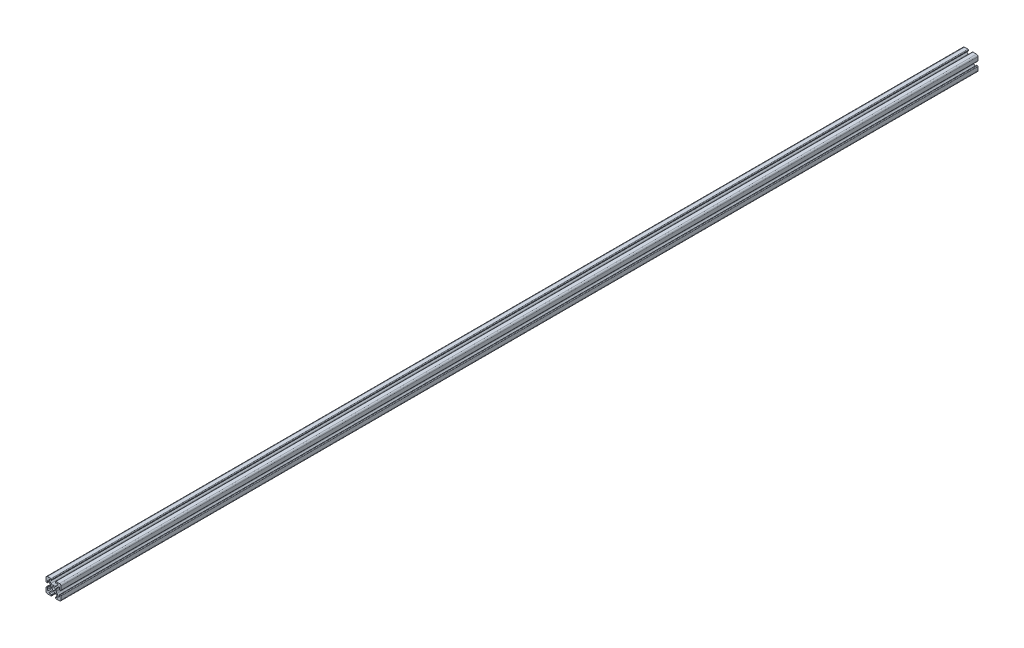
SolidWorks part; units mm, degrees
ref_plane "Front Plane" through (0, 0, 0) normal (0, 0, 1) x (1, 0, 0)
ref_plane "Top Plane" through (0, 0, 0) normal (0, 1, 0) x (1, 0, 0)
ref_plane "Right Plane" through (0, 0, 0) normal (1, 0, 0) x (0, 0, -1)
sketch "Sketch1" plane through (0, 0, 0) normal (0, 0, 1) x (1, 0, 0)
  line L2 (-9.9949, 7.9883) -> (-9.9949, 3.2893)
  line L3 (-7.9883, 9.9949) -> (-3.2893, 9.9949)
  line L4 (-2.5019, 9.2075) -> (-2.5019, 8.4963)
  line L5 (-2.8067, 8.1915) -> (-4.9149, 8.1915)
  line L6 (-5.5076, 6.7606) -> (-3.2528, 4.5058)
  line L7 (-6.7606, 5.5076) -> (-4.5058, 3.2528)
  line L8 (-8.1915, 4.9149) -> (-8.1915, 2.8067)
  line L9 (-8.4963, 2.5019) -> (-9.2075, 2.5019)
  line L11 (-1.1334, 3.6279) -> (1.1334, 3.6279)
  line L12 (-3.6279, 1.1334) -> (-3.6279, -1.1334)
  line L13 (8.4963, 2.5019) -> (9.2075, 2.5019)
  line L14 (8.1915, 4.9149) -> (8.1915, 2.8067)
  line L15 (9.9949, 7.9883) -> (9.9949, 3.2893)
  line L16 (7.9883, 9.9949) -> (3.2893, 9.9949)
  line L17 (2.5019, 9.2075) -> (2.5019, 8.4963)
  line L18 (2.8067, 8.1915) -> (4.9149, 8.1915)
  line L19 (3.6279, 1.1334) -> (3.6279, -1.1334)
  line L20 (5.5076, 6.7606) -> (3.2528, 4.5058)
  line L21 (6.7606, 5.5076) -> (4.5058, 3.2528)
  line L22 (-8.4963, -2.5019) -> (-9.2075, -2.5019)
  line L23 (-8.1915, -4.9149) -> (-8.1915, -2.8067)
  line L24 (-6.7606, -5.5076) -> (-4.5058, -3.2528)
  line L25 (-5.5076, -6.7606) -> (-3.2528, -4.5058)
  line L26 (-2.8067, -8.1915) -> (-4.9149, -8.1915)
  line L27 (-2.5019, -9.2075) -> (-2.5019, -8.4963)
  line L28 (-7.9883, -9.9949) -> (-3.2893, -9.9949)
  line L29 (-9.9949, -7.9883) -> (-9.9949, -3.2893)
  line L30 (9.9949, -7.9883) -> (9.9949, -3.2893)
  line L31 (7.9883, -9.9949) -> (3.2893, -9.9949)
  line L32 (2.5019, -9.2075) -> (2.5019, -8.4963)
  line L33 (2.8067, -8.1915) -> (4.9149, -8.1915)
  line L34 (5.5076, -6.7606) -> (3.2528, -4.5058)
  line L35 (6.7606, -5.5076) -> (4.5058, -3.2528)
  line L36 (8.1915, -4.9149) -> (8.1915, -2.8067)
  line L37 (8.4963, -2.5019) -> (9.2075, -2.5019)
  line L38 (-1.1334, -3.6279) -> (1.1334, -3.6279)
  circle A0 centre (0, 0) radius 2.1463
  arc A1 (-9.9949, 7.9883) -> (-7.9883, 9.9949) centre (-7.9883, 7.9883) cw
  arc A2 (-6.7606, 5.5076) -> (-8.1915, 4.9149) centre (-7.3533, 4.9149) ccw
  arc A3 (-4.9149, 8.1915) -> (-5.5076, 6.7606) centre (-4.9149, 7.3533) ccw
  arc A4 (-3.2893, 9.9949) -> (-2.5019, 9.2075) centre (-3.2893, 9.2075) cw
  arc A5 (-9.9949, 3.2893) -> (-9.2075, 2.5019) centre (-9.2075, 3.2893) ccw
  arc A6 (-8.1915, 2.8067) -> (-8.4963, 2.5019) centre (-8.4963, 2.8067) cw
  arc A7 (-2.5019, 8.4963) -> (-2.8067, 8.1915) centre (-2.8067, 8.4963) cw
  arc A8 (-1.1334, 3.6279) -> (-3.2528, 4.5058) centre (-1.1334, 6.6251) cw
  arc A9 (-3.6279, 1.1334) -> (-4.5058, 3.2528) centre (-6.6251, 1.1334) ccw
  arc A10 (8.1915, 2.8067) -> (8.4963, 2.5019) centre (8.4963, 2.8067) ccw
  arc A11 (9.9949, 3.2893) -> (9.2075, 2.5019) centre (9.2075, 3.2893) cw
  arc A12 (9.9949, 7.9883) -> (7.9883, 9.9949) centre (7.9883, 7.9883) ccw
  arc A13 (3.2893, 9.9949) -> (2.5019, 9.2075) centre (3.2893, 9.2075) ccw
  arc A14 (2.5019, 8.4963) -> (2.8067, 8.1915) centre (2.8067, 8.4963) ccw
  arc A15 (1.1334, 3.6279) -> (3.2528, 4.5058) centre (1.1334, 6.6251) ccw
  arc A16 (3.6279, 1.1334) -> (4.5058, 3.2528) centre (6.6251, 1.1334) cw
  arc A17 (6.7606, 5.5076) -> (8.1915, 4.9149) centre (7.3533, 4.9149) cw
  arc A18 (4.9149, 8.1915) -> (5.5076, 6.7606) centre (4.9149, 7.3533) cw
  arc A19 (-3.6279, -1.1334) -> (-4.5058, -3.2528) centre (-6.6251, -1.1334) cw
  arc A20 (-1.1334, -3.6279) -> (-3.2528, -4.5058) centre (-1.1334, -6.6251) ccw
  arc A21 (-2.5019, -8.4963) -> (-2.8067, -8.1915) centre (-2.8067, -8.4963) ccw
  arc A22 (-8.1915, -2.8067) -> (-8.4963, -2.5019) centre (-8.4963, -2.8067) ccw
  arc A23 (-9.9949, -3.2893) -> (-9.2075, -2.5019) centre (-9.2075, -3.2893) cw
  arc A24 (-3.2893, -9.9949) -> (-2.5019, -9.2075) centre (-3.2893, -9.2075) ccw
  arc A25 (-4.9149, -8.1915) -> (-5.5076, -6.7606) centre (-4.9149, -7.3533) cw
  arc A26 (-6.7606, -5.5076) -> (-8.1915, -4.9149) centre (-7.3533, -4.9149) cw
  arc A27 (-9.9949, -7.9883) -> (-7.9883, -9.9949) centre (-7.9883, -7.9883) ccw
  arc A28 (9.9949, -7.9883) -> (7.9883, -9.9949) centre (7.9883, -7.9883) cw
  arc A29 (6.7606, -5.5076) -> (8.1915, -4.9149) centre (7.3533, -4.9149) ccw
  arc A30 (4.9149, -8.1915) -> (5.5076, -6.7606) centre (4.9149, -7.3533) ccw
  arc A31 (3.2893, -9.9949) -> (2.5019, -9.2075) centre (3.2893, -9.2075) cw
  arc A32 (9.9949, -3.2893) -> (9.2075, -2.5019) centre (9.2075, -3.2893) ccw
  arc A33 (8.1915, -2.8067) -> (8.4963, -2.5019) centre (8.4963, -2.8067) cw
  arc A34 (2.5019, -8.4963) -> (2.8067, -8.1915) centre (2.8067, -8.4963) cw
  arc A35 (1.1334, -3.6279) -> (3.2528, -4.5058) centre (1.1334, -6.6251) cw
  arc A36 (3.6279, -1.1334) -> (4.5058, -3.2528) centre (6.6251, -1.1334) ccw
extrude "Boss-Extrude1" add sketch "Sketch1" along normal mid plane 1219.2
